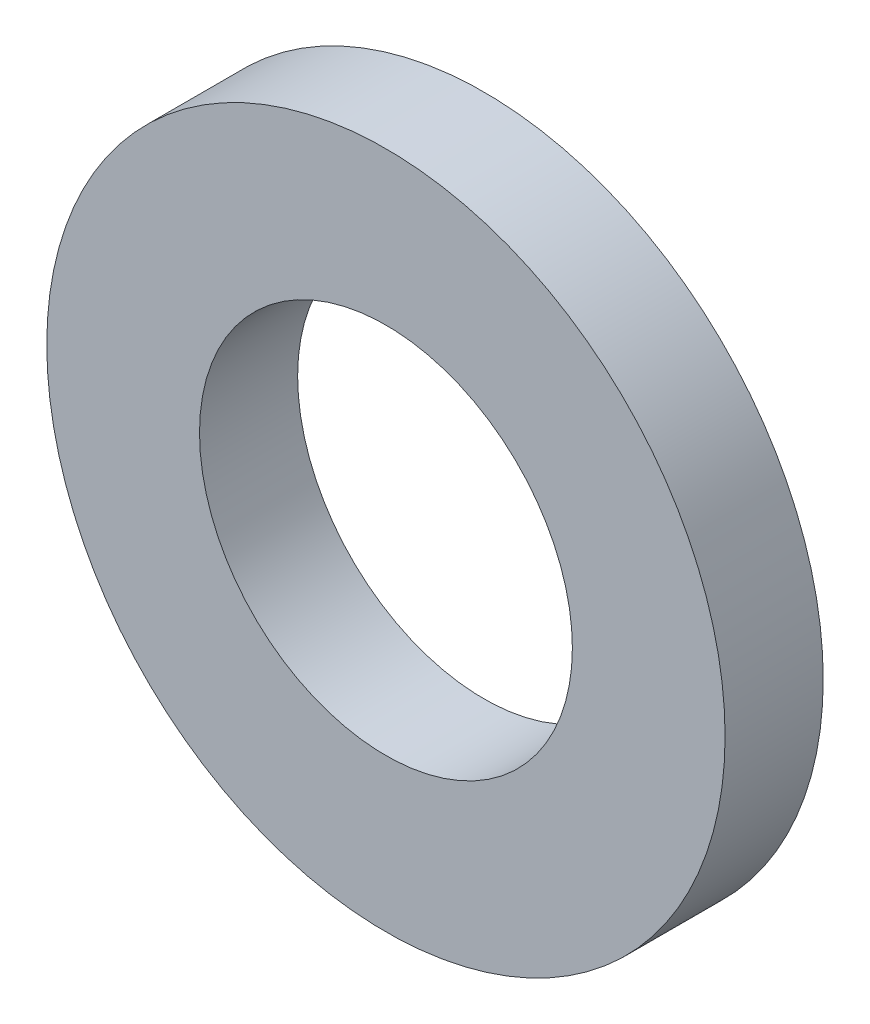
SolidWorks part; units mm, degrees
ref_plane "Front Plane" through (0, 0, 0) normal (0, 0, 1) x (1, 0, 0)
ref_plane "Top Plane" through (0, 0, 0) normal (0, 1, 0) x (1, 0, 0)
ref_plane "Right Plane" through (0, 0, 0) normal (1, 0, 0) x (0, 0, -1)
sketch "Sketch1" plane through (0, 0, 0) normal (0, 0, 1) x (1, 0, 0)
  circle A0 centre (0, 0) radius 3.4565
  circle A1 centre (0, 0) radius 1.9
  dimension "D1" = 3.8
extrude "Boss-Extrude1" add sketch "Sketch1" along normal blind 1
